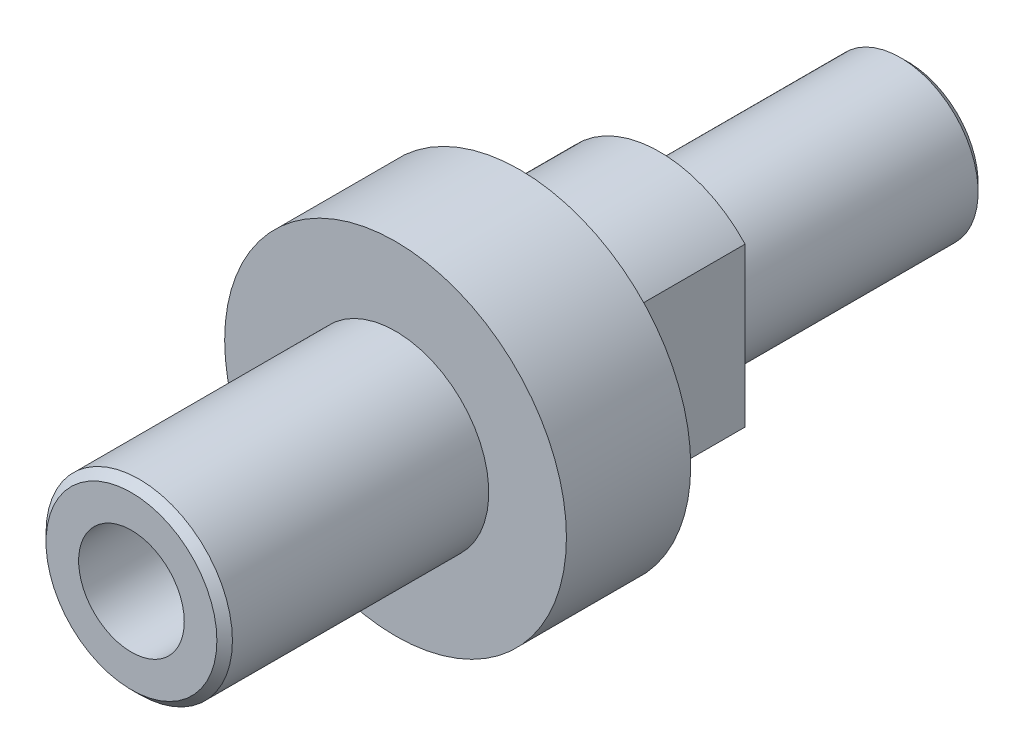
SolidWorks part; units mm, degrees
ref_plane "前视基准面" through (0, 0, 0) normal (0, 0, 1) x (1, 0, 0)
ref_plane "上视基准面" through (0, 0, 0) normal (0, 1, 0) x (1, 0, 0)
ref_plane "右视基准面" through (0, 0, 0) normal (1, 0, 0) x (0, 0, -1)
sketch "草图1" plane through (0, 0, 0) normal (1, 0, 0) x (0, 0, -1)
  line L0 (0, 6) -> (17, 6)
  line L1 (17, 6) -> (17, 11)
  line L2 (17, 11) -> (25, 11)
  line L3 (25, 11) -> (25, 7.5)
  line L4 (25, 7.5) -> (34, 7.5)
  line L5 (34, 7.5) -> (34, 5)
  line L6 (34, 5) -> (50, 5)
  line L7 (50, 5) -> (50, 0)
  line L8 (50, 0) -> (0, 0)
  line L9 (0, 0) -> (0, 6)
  dimension "D1" = 6
  dimension "D2" = 11
  dimension "D3" = 17
  dimension "D4" = 8
  dimension "D5" = 9
  dimension "D6" = 7.5
  dimension "D7" = 5
  dimension "D8" = 16
revolve "旋转1" add sketch "草图1" angle 360 about L8
cosmetic thread "装饰螺纹线1" parameters "D2"=8
sketch "草图2" plane through (0, 0, -34) normal (0, 0, 1) x (1, 0, 0)
  line L0 (0, 0) -> (0, 8.626) construction
  line L1 (-5.5, 8.5852) -> (5.5, 8.5852)
  line L2 (-5.5, 8.5852) -> (-5.5, -9.0424)
  line L3 (-5.5, -9.0424) -> (5.5, -9.0424)
  line L4 (5.5, 8.5852) -> (5.5, -9.0424)
  dimension "D1" = 11
extrude "切除-拉伸1" cut sketch "草图2" along normal up to surface (9 mm away) flip side to cut up to face at (-11, 0, -25)
hole_wizard "M8x1.25 螺纹孔1" positions "草图4" profile "草图3" tap size "M8x1.25" standard "JIS"
sketch "草图4" plane through (0, 0, 0) normal (0, 0, 1) x (1, 0, 0)
  point P1 (0, 0)
sketch "草图3" plane through (0, 0, 0) normal (1, 0, 0) x (0, -1, 0)
  line L0 (0, 0) -> (0, 21.7929)
  line L1 (0, 21.7929) -> (3.4, 19.75)
  line L2 (3.4, 19.75) -> (3.4, 0)
  line L5 (3.4, 0) -> (0, 0)
  line L10 (0, 21.7929) -> (-3.4, 19.75) construction
  line L11 (0, -6.35) -> (0, 107.95) construction
  dimension "螺纹孔钻头直径" = 6.8
  dimension "螺纹孔钻头深度" = 19.75
  dimension "导头角度" = 118
cosmetic thread "孔螺蚊线1" parameters "D1"=16, "D2"=8
chamfer "倒角1" distance 0.5 angle 45 2 edges at (-5, 0, -50) (-6, 0, 0)
